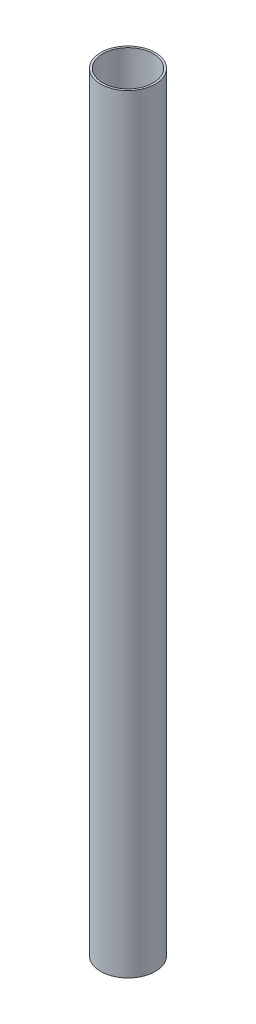
SolidWorks part; units mm, degrees
material "Plástico personalizado"
ref_plane "Plano frontal" through (0, 0, 0) normal (0, 0, 1) x (1, 0, 0)
ref_plane "Plano superior" through (0, 0, 0) normal (0, 1, 0) x (1, 0, 0)
ref_plane "Plano direito" through (0, 0, 0) normal (1, 0, 0) x (0, 0, -1)
sketch "Esboço1" plane through (0, 0, 0) normal (0, 1, 0) x (1, 0, 0)
  circle A0 centre (0, 0) radius 27
  circle A1 centre (0, 0) radius 25
extrude "Ressalto-extrusão1" add sketch "Esboço1" along normal blind 760 contours A0 | A1
